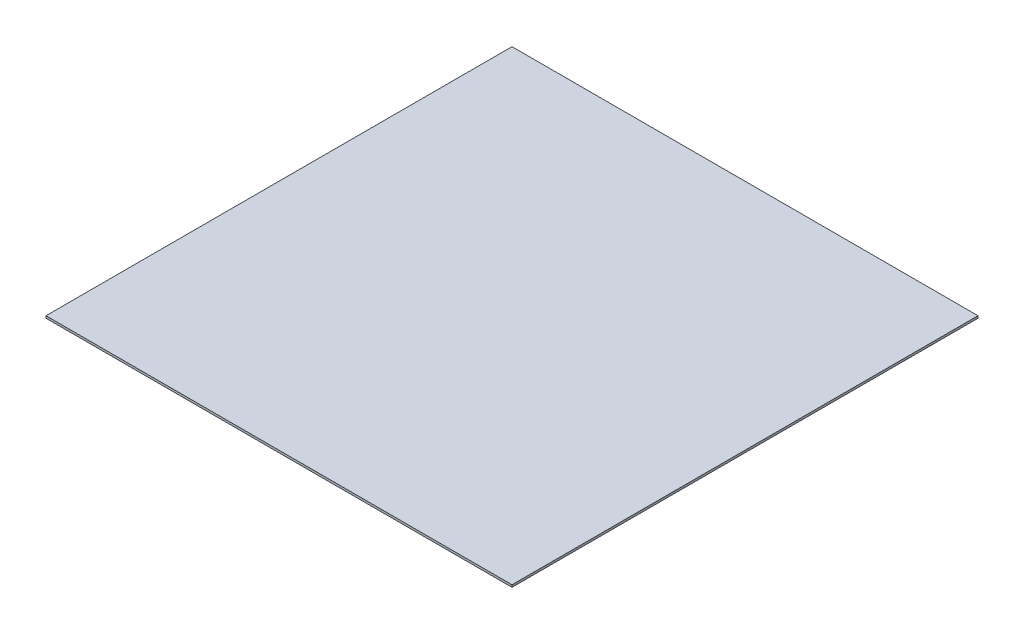
SolidWorks part; units mm, degrees
material "6061-T6 (SS)"
ref_plane "Front Plane" through (0, 0, 0) normal (0, 0, 1) x (1, 0, 0)
ref_plane "Top Plane" through (0, 0, 0) normal (0, 1, 0) x (1, 0, 0)
ref_plane "Right Plane" through (0, 0, 0) normal (1, 0, 0) x (0, 0, -1)
sketch "Sketch1" plane through (0, 0, 0) normal (0, 1, 0) x (1, 0, 0)
  line L1 (0, 0) -> (2000, 0)
  line L2 (0, 0) -> (0, -2000)
  line L3 (0, -2000) -> (2000, -2000)
  line L4 (2000, 0) -> (2000, -2000)
  dimension "D1" = 2000
  dimension "D2" = 2000
extrude "Boss-Extrude1" add sketch "Sketch1" along normal blind 9.525
sketch "Sketch3" plane through (0, 0, 0) normal (0, -1, 0) x (1, 0, 0)
  line L0 (0, 2000) -> (2000, 0) construction
  line L1 (0, 0) -> (2000, 2000) construction
  line L3 (2000, 0) -> (0, 0) construction
  line L5 (2000, 2000) -> (2000, 0) construction
  line L7 (0, 0) -> (0, 2000) construction
  line L9 (0, 2000) -> (2000, 2000) construction
  line L10 (1000, 500) -> (1000, 0) construction
  line L11 (1500, 1000) -> (2000, 1000)
  line L12 (500, 1000) -> (0, 1000)
  line L13 (1000, 1500) -> (1000, 2000)
  point P8 (1000, 1000)
  point P9 (1000, 250)
  point P13 (1000, 500)
  point P23 (1500, 1000)
  point P24 (500, 1000)
  point P25 (1000, 1500)
  point P30 (250, 1000)
  point P31 (1000, 1750)
  point P32 (1750, 1000)
